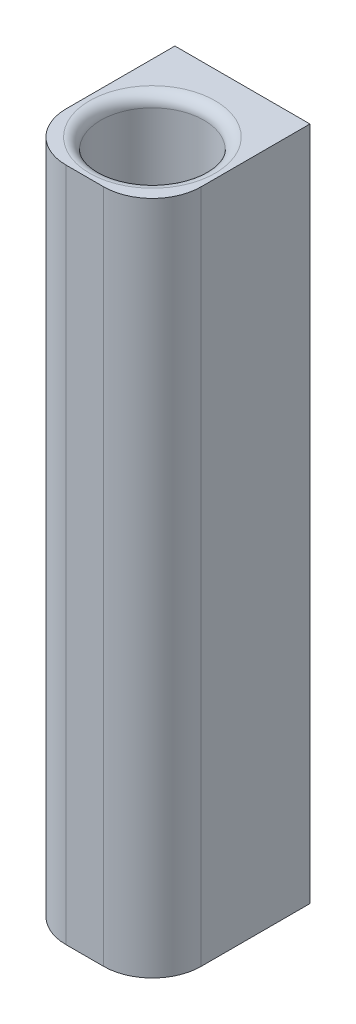
SolidWorks part; units mm, degrees
ref_plane "Front Plane" through (0, 0, 0) normal (0, 0, 1) x (1, 0, 0)
ref_plane "Top Plane" through (0, 0, 0) normal (0, 1, 0) x (1, 0, 0)
ref_plane "Right Plane" through (0, 0, 0) normal (1, 0, 0) x (0, 0, -1)
sketch "Sketch1" plane through (0, 0, 0) normal (0, 1, 0) x (1, 0, 0)
  line L0 (0, 29.8372) -> (-18, 29.8372)
  line L10 (18, 29.8372) -> (0, 29.8372)
  line L11 (-18, 29.8372) -> (-18, -12.1628)
  line L12 (-18, -12.1628) -> (18, -12.1628)
  line L13 (18, -12.1628) -> (18, 29.8372)
  line L14 (0, 29.8372) -> (0, 0) construction
  circle A0 centre (0, 5.8372) radius 13.75
  point P0 (0, 0)
  dimension "D1" = 27.5
  dimension "D2" = 24
  dimension "D3" = 18
  dimension "D4" = 18
  dimension "D5" = 18
extrude "Boss-Extrude1" add sketch "Sketch1" along normal blind 180
fillet "Fillet1" radius 13 2 edges at (-18, 90, 12.1628) (18, 90, 12.1628)
fillet "Fillet2" radius 3 2 edges at (0, 0, 7.9128) (0, 180, 7.9128)
